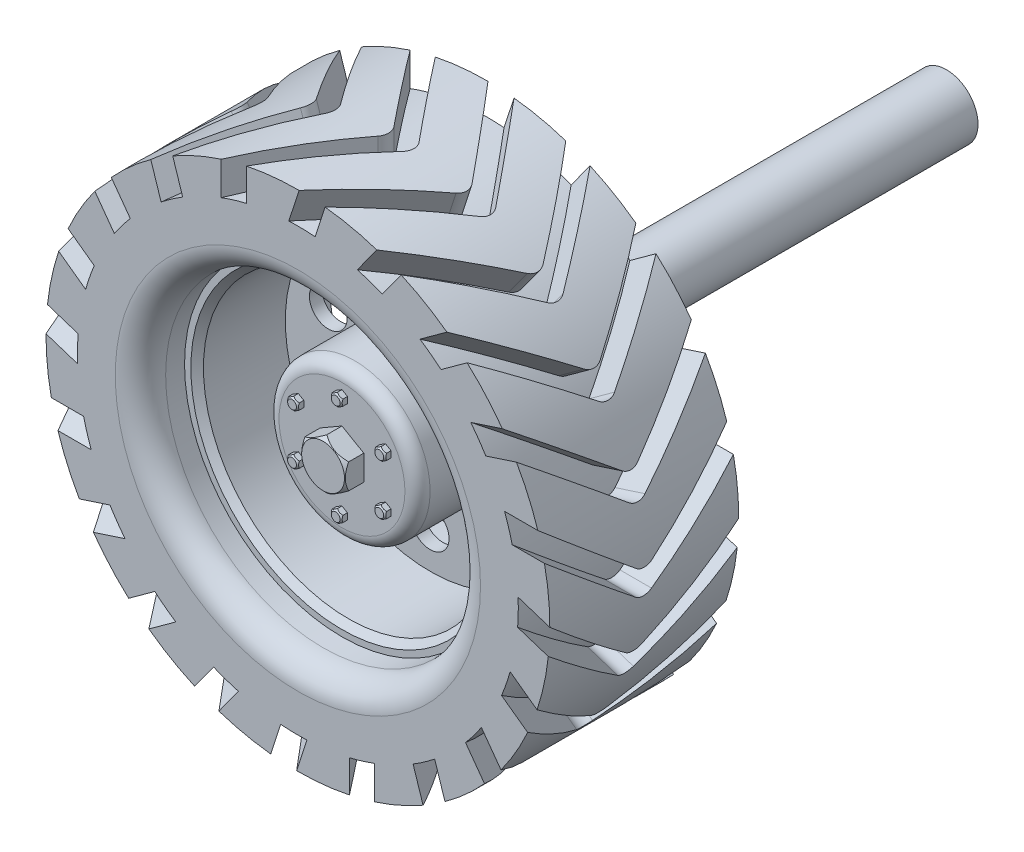
SolidWorks part; units mm, degrees
ref_plane "前基準面" through (0, 0, 0) normal (0, 0, 1) x (1, 0, 0)
ref_plane "上基準面" through (0, 0, 0) normal (0, 1, 0) x (1, 0, 0)
ref_plane "右基準面" through (0, 0, 0) normal (1, 0, 0) x (0, 0, -1)
sketch "草圖1" plane through (0, 0, 0) normal (0, 0, 1) x (1, 0, 0)
  circle A0 centre (0, 0) radius 125
  dimension "D1" = 250
extrude "填料-伸長1" add sketch "草圖1" along normal mid plane 80
shell "薄殼1" thickness 10
sketch "草圖3" plane through (0, 0, 0) normal (0, 0, 1) x (1, 0, 0)
  circle A0 centre (0, 0) radius 200
  circle A1 centre (0, 0) radius 125
  dimension "D1" = 400
  dimension "D2" = 250
extrude "填料-伸長2" add sketch "草圖3" along normal mid plane 150
chamfer "導角1" distance 5 angle 45 1 edges at (115, 0, 40)
fillet "圓角2" radius 20 1 edges at (125, 0, 75)
sketch "草圖4" plane through (0, 0, -30) normal (0, 0, 1) x (1, 0, 0)
  circle A0 centre (0, 0) radius 60
  dimension "D1" = 120
extrude "填料-伸長3" add sketch "草圖4" along normal up to surface (70 mm away) up to face at (120, 0, 40)
fillet "圓角4" radius 10 1 edges at (60, 0, 40)
sketch "草圖5" plane through (0, 0, -30) normal (0, 0, 1) x (1, 0, 0)
  line L0 (0, 0) -> (0, 85) construction
  circle A0 centre (0, 85) radius 15
  dimension "D1" = 30
  dimension "D2" = 85
extrude "除料-伸長2" cut sketch "草圖5" against normal blind 100
pattern_circular "環狀複製排列1" count 10 over 360 about axis through (0, 0, 0) along (0, 0, 1) of "除料-伸長2"
fillet "圓角5" radius 5 1 edges at (60, 0, -30)
sketch "草圖7" plane through (0, 0, 40) normal (0, 0, 1) x (1, 0, 0)
  circle A0 centre (0, 0) radius 20
  dimension "D1" = 40
extrude "填料-伸長5" add sketch "草圖7" along normal blind 15
chamfer "導角2" distance 3 angle 45 1 edges at (20, 0, 55)
sketch "草圖8" plane through (0, 0, 55) normal (0, 0, 1) x (1, 0, 0)
  line L1 (0, 20) -> (-17.3205, 10)
  line L2 (-17.3205, 10) -> (-17.3205, -10)
  line L3 (-17.3205, -10) -> (0, -20)
  line L4 (0, -20) -> (17.3205, -10)
  line L5 (17.3205, -10) -> (17.3205, 10)
  line L6 (17.3205, 10) -> (0, 20)
  circle A0 centre (0, 0) radius 17.3205 construction
  circle A1 centre (0, 0) radius 20
extrude "除料-伸長3" cut sketch "草圖8" against normal blind 15 contours L1 A1 | L6 A1 | L2 A1 | L3 A1 | L4 A1 | L5 A1
sketch "草圖9" plane through (0, 0, 40) normal (0, 0, 1) x (1, 0, 0)
  circle A0 centre (0, 0) radius 40 construction
  circle A1 centre (0, 40) radius 5
  dimension "D1" = 80
  dimension "D2" = 10
extrude "填料-伸長6" add sketch "草圖9" along normal blind 5
chamfer "導角3" distance 1.5 angle 45 1 edges at (5, 40, 45)
pattern_circular "環狀複製排列2" count 6 over 360 about axis through (0, 0, 0) along (0, 0, 1) of "填料-伸長6"
chamfer "導角4" distance 1.5 angle 45 5 edges at (37.141, 15.6699, 45) (32.141, -24.3301, 45) (-5, -40, 45) (-37.141, -15.6699, 45) (-32.141, 24.3301, 45)
sketch "草圖10" plane through (0, 0, 45) normal (0, 0, 1) x (1, 0, 0)
  line L1 (0, 45) -> (-4.3301, 42.5)
  line L2 (-4.3301, 42.5) -> (-4.3301, 37.5)
  line L3 (-4.3301, 37.5) -> (0, 35)
  line L4 (0, 35) -> (4.3301, 37.5)
  line L5 (4.3301, 37.5) -> (4.3301, 42.5)
  line L6 (4.3301, 42.5) -> (0, 45)
  circle A0 centre (0, 40) radius 4.3301 construction
  circle A1 centre (0, 40) radius 5
extrude "除料-伸長4" cut sketch "草圖10" against normal blind 5 contours L1 A1 | L6 A1 | L2 A1 | L3 A1 | L4 A1 | L5 A1
pattern_circular "環狀複製排列4" count 6 over 360 about axis through (0, 0, 0) along (0, 0, 1) of "除料-伸長4"
ref_plane "平面1" through (0, 300, 0) normal (0, 1, 0) x (1, 0, 0)
sketch "草圖11" plane through (0, 300, 0) normal (0, 1, 0) x (1, 0, 0)
  line L1 (-5.1172, -6.303) -> (-60.8905, -75)
  line L2 (0, 0) -> (20, 0) construction
  line L8 (-200, -75) -> (200, -75) construction
  line L9 (-5.1172, 6.303) -> (-60.8905, 75)
  line L10 (200, 75) -> (-200, 75) construction
  line L11 (-60.8905, 75) -> (-60.8905, -75) construction
  line L16 (14.8828, -6.303) -> (-40.8905, -75)
  line L17 (14.8828, 6.303) -> (-40.8905, 75)
  line L18 (-60.8905, -75) -> (-40.8905, -75)
  line L19 (-60.8905, 75) -> (-40.8905, 75)
  arc A0 (14.8828, -6.303) -> (14.8828, 6.303) centre (7.1192, 0) ccw
  arc A1 (-5.1172, -6.303) -> (-5.1172, 6.303) centre (-12.8808, 0) ccw
  dimension "D2" = 10
  dimension "D1" = 20
sketch "草圖13" plane through (0, 0, 75) normal (0, 0, 1) x (1, 0, 0)
  circle A0 centre (0, 0) radius 175
  dimension "D1" = 350
surface "曲面-伸長1" sketch "草圖13" parameters "D1"=176
extrude "除料-伸長5" cut sketch "草圖11" against normal up to surface (125.0748 mm away)
pattern_circular "環狀複製排列6" count 20 over 360 about axis through (0, 0, 0) along (0, 0, 1) of "除料-伸長5"
sketch "草圖14" plane through (0, 0, -40) normal (0, 0, -1) x (-1, 0, 0)
  circle A0 centre (0, 0) radius 25
  dimension "D1" = 50
extrude "填料-伸長7" add sketch "草圖14" along normal blind 400
